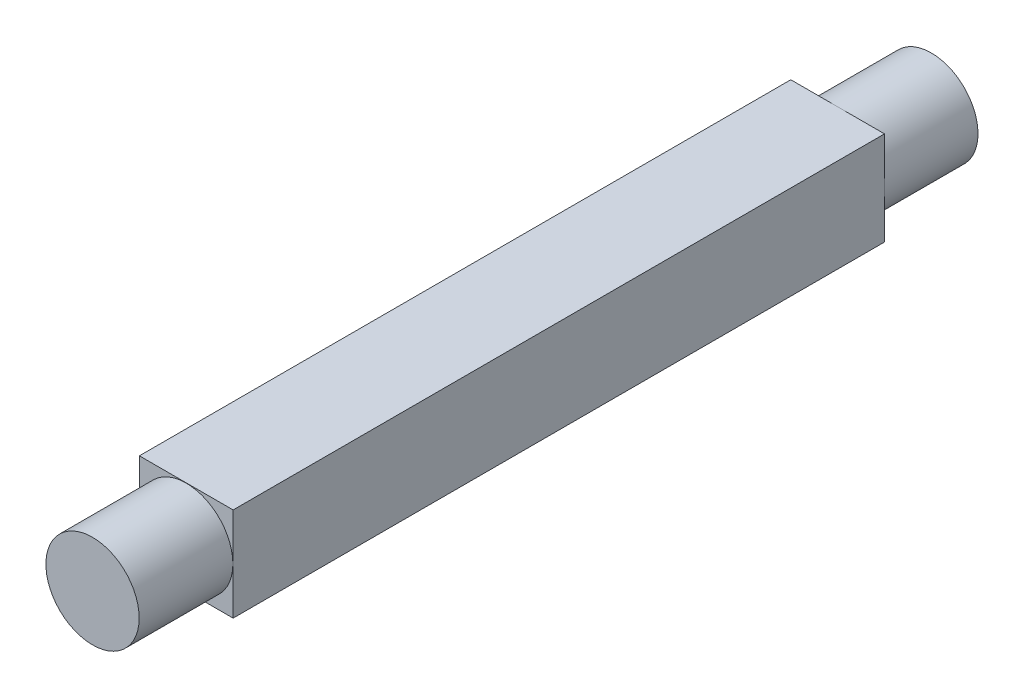
SolidWorks part; units mm, degrees
ref_plane "Front Plane" through (0, 0, 0) normal (0, 0, 1) x (1, 0, 0)
ref_plane "Top Plane" through (0, 0, 0) normal (0, 1, 0) x (1, 0, 0)
ref_plane "Right Plane" through (0, 0, 0) normal (1, 0, 0) x (0, 0, -1)
sketch "Sketch1" plane through (0, 0, 0) normal (0, 0, 1) x (1, 0, 0)
  line L1 (2, -2) -> (-2, -2)
  line L2 (2, -2) -> (2, 2)
  line L3 (2, 2) -> (-2, 2)
  line L4 (-2, -2) -> (-2, 2)
  line L5 (2, -2) -> (-2, 2) construction
  line L6 (2, 2) -> (-2, -2) construction
  dimension "D2" = 4
extrude "Boss-Extrude1" add sketch "Sketch1" along normal mid plane 27.8
sketch "Sketch2" plane through (0, 0, 13.9) normal (0, 0, 1) x (1, 0, 0)
  circle A0 centre (0, 0) radius 1.99
  dimension "D1" = 3.98
extrude "Boss-Extrude2" add sketch "Sketch2" along normal blind 4
mirror "Mirror2" about plane through (0, 0, 0) normal (0, 0, 1) of "Boss-Extrude2"
